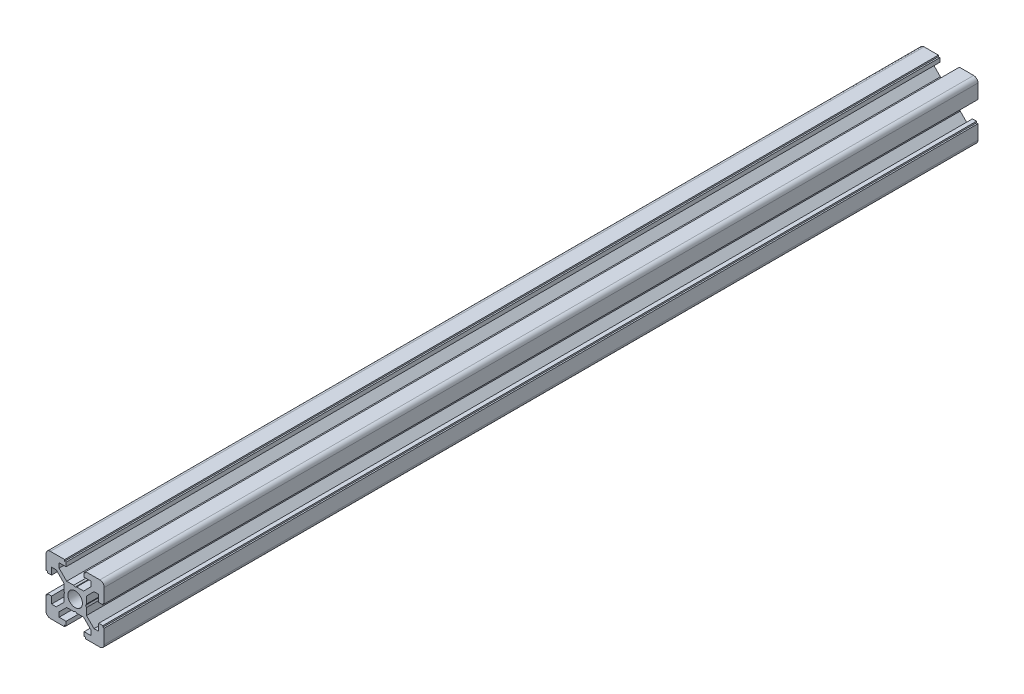
SolidWorks part; units mm, degrees
ref_plane "前视基准面" through (0, 0, 0) normal (0, 0, 1) x (1, 0, 0)
ref_plane "上视基准面" through (0, 0, 0) normal (0, 1, 0) x (1, 0, 0)
ref_plane "右视基准面" through (0, 0, 0) normal (1, 0, 0) x (0, 0, -1)
sketch "草图28" plane through (0, 0, 0) normal (0, 0, 1) x (1, 0, 0)
  line B0 (0, 11.0182) -> (0, -11.0182) construction
  line B1 (-11.0182, 0) -> (11.0182, 0) construction
  line B2 (-3.9, -0.5196) -> (-3.9, -2.9101)
  line B3 (-3.9, -2.9101) -> (-6.4899, -5.5)
  line B4 (-6.4899, -5.5) -> (-8.1, -5.5)
  line B5 (-8.1, -5.5) -> (-8.1, -3.1)
  line B6 (-8.1, -3.1) -> (-9.5, -3.1)
  line B7 (-9.5, -3.1) -> (-9.5, -3.6)
  line B8 (-9.5, -3.6) -> (-10, -3.6)
  line B9 (-10, -3.6) -> (-10, -8.5)
  line B10 (-8.5, -10) -> (-3.6, -10)
  line B11 (-3.6, -10) -> (-3.6, -9.5)
  line B12 (-3.6, -9.5) -> (-3.1, -9.5)
  line B13 (-3.1, -9.5) -> (-3.1, -8.1)
  line B14 (-3.1, -8.1) -> (-5.5, -8.1)
  line B15 (-5.5, -8.1) -> (-5.5, -6.4899)
  line B16 (-5.5, -6.4899) -> (-2.9101, -3.9)
  line B17 (-2.9101, -3.9) -> (-0.5196, -3.9)
  line B18 (-0.5196, -3.9) -> (0, -3.6)
  line B19 (0, -3.6) -> (0.5196, -3.9)
  line B20 (0.5196, -3.9) -> (2.9101, -3.9)
  line B21 (2.9101, -3.9) -> (5.5, -6.4899)
  line B22 (5.5, -6.4899) -> (5.5, -8.1)
  line B23 (5.5, -8.1) -> (3.1, -8.1)
  line B24 (3.1, -8.1) -> (3.1, -9.5)
  line B25 (3.1, -9.5) -> (3.6, -9.5)
  line B26 (3.6, -9.5) -> (3.6, -10)
  line B27 (3.6, -10) -> (8.5, -10)
  line B28 (10, -8.5) -> (10, -3.6)
  line B29 (10, -3.6) -> (9.5, -3.6)
  line B30 (9.5, -3.6) -> (9.5, -3.1)
  line B31 (9.5, -3.1) -> (8.1, -3.1)
  line B32 (8.1, -3.1) -> (8.1, -5.5)
  line B33 (8.1, -5.5) -> (6.4899, -5.5)
  line B34 (6.4899, -5.5) -> (3.9, -2.9101)
  line B35 (3.9, -2.9101) -> (3.9, -0.5196)
  line B36 (3.9, -0.5196) -> (3.6, 0)
  line B37 (3.6, 0) -> (3.9, 0.5196)
  line B38 (3.9, 0.5196) -> (3.9, 2.9101)
  line B39 (3.9, 2.9101) -> (6.4899, 5.5)
  line B40 (6.4899, 5.5) -> (8.1, 5.5)
  line B41 (8.1, 5.5) -> (8.1, 3.1)
  line B42 (8.1, 3.1) -> (9.5, 3.1)
  line B43 (9.5, 3.1) -> (9.5, 3.6)
  line B44 (9.5, 3.6) -> (10, 3.6)
  line B45 (10, 3.6) -> (10, 8.5)
  line B46 (8.5, 10) -> (3.6, 10)
  line B47 (3.6, 10) -> (3.6, 9.5)
  line B48 (3.6, 9.5) -> (3.1, 9.5)
  line B49 (3.1, 9.5) -> (3.1, 8.1)
  line B50 (3.1, 8.1) -> (5.5, 8.1)
  line B51 (5.5, 8.1) -> (5.5, 6.4899)
  line B52 (5.5, 6.4899) -> (2.9101, 3.9)
  line B53 (2.9101, 3.9) -> (0.5196, 3.9)
  line B54 (0.5196, 3.9) -> (0, 3.6)
  line B55 (0, 3.6) -> (-0.5196, 3.9)
  line B56 (-0.5196, 3.9) -> (-2.9101, 3.9)
  line B57 (-2.9101, 3.9) -> (-5.5, 6.4899)
  line B58 (-5.5, 6.4899) -> (-5.5, 8.1)
  line B59 (-5.5, 8.1) -> (-3.1, 8.1)
  line B60 (-3.1, 8.1) -> (-3.1, 9.5)
  line B61 (-3.1, 9.5) -> (-3.6, 9.5)
  line B62 (-3.6, 9.5) -> (-3.6, 10)
  line B63 (-3.6, 10) -> (-8.5, 10)
  line B64 (-10, 8.5) -> (-10, 3.6)
  line B65 (-10, 3.6) -> (-9.5, 3.6)
  line B66 (-9.5, 3.6) -> (-9.5, 3.1)
  line B67 (-9.5, 3.1) -> (-8.1, 3.1)
  line B68 (-8.1, 3.1) -> (-8.1, 5.5)
  line B69 (-8.1, 5.5) -> (-6.4899, 5.5)
  line B70 (-6.4899, 5.5) -> (-3.9, 2.9101)
  line B71 (-3.9, 2.9101) -> (-3.9, 0.5196)
  line B72 (-3.9, 0.5196) -> (-3.6, 0)
  line B73 (-3.6, 0) -> (-3.9, -0.5196)
  circle B74 centre (0, 0) radius 2.5
  arc B75 (-10, -8.5) -> (-8.5, -10) centre (-8.5, -8.5) ccw
  arc B76 (8.5, -10) -> (10, -8.5) centre (8.5, -8.5) ccw
  arc B77 (10, 8.5) -> (8.5, 10) centre (8.5, 8.5) ccw
  arc B78 (-8.5, 10) -> (-10, 8.5) centre (-8.5, 8.5) ccw
sketch_block_instance "块1-1"
sketch_block "块1"
extrude "凸台-拉伸1" add sketch "草图28" along normal blind 300
cosmetic thread "装饰螺纹线1" [suppressed]
cosmetic thread "装饰螺纹线2" [suppressed]
equation "\"length\"= 300mm"
